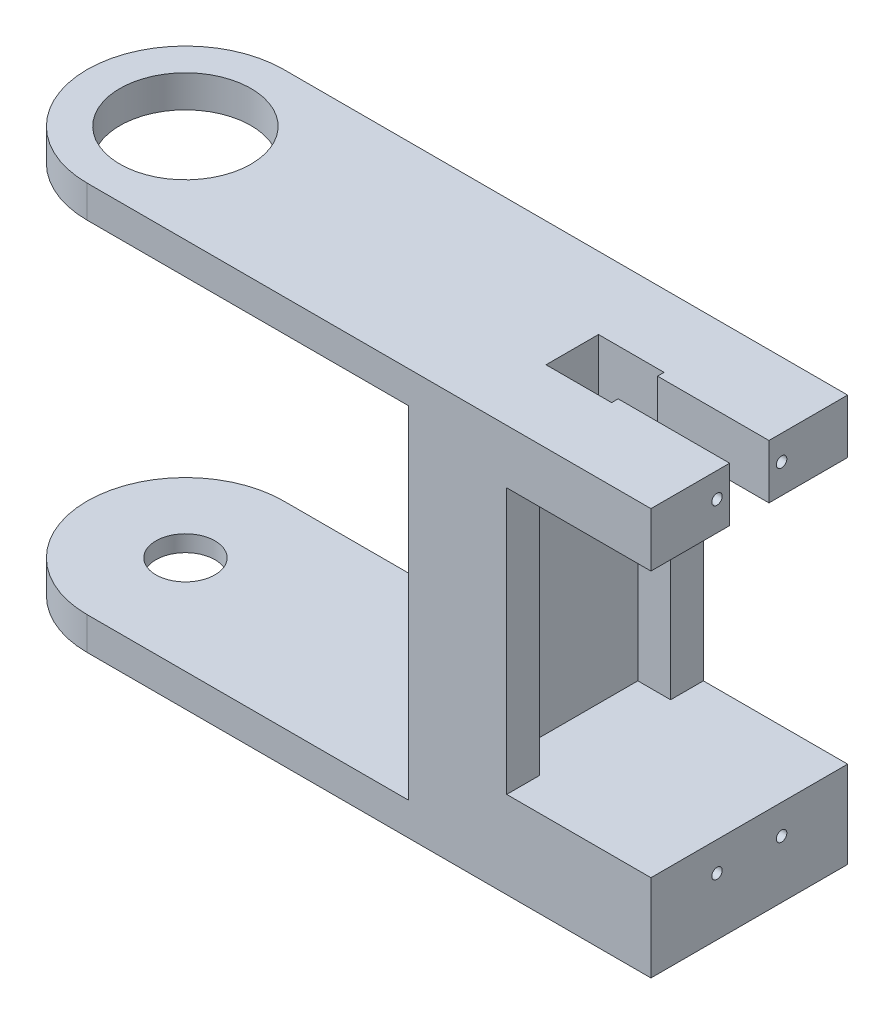
SolidWorks part; units mm, degrees
other "Marquage1"
sketch "Esquisse9" plane through (30.25, -27, 30) normal (0.9363, -0.2766, 0.2166) x (0.221, -0.0157, -0.9752)
ref_plane "Plan de face" through (0, 0, 0) normal (0, 0, 1) x (1, 0, 0)
ref_plane "Plan de dessus" through (0, 0, 0) normal (0, 1, 0) x (1, 0, 0)
ref_plane "Plan de droite" through (0, 0, 0) normal (1, 0, 0) x (0, 0, -1)
sketch "Esquisse1" plane through (0, 0, 0) normal (0, 0, 1) x (1, 0, 0)
  line L1 (-30.25, 32) -> (30.25, 32)
  line L2 (-30.25, 32) -> (-30.25, -32)
  line L3 (-30.25, -32) -> (30.25, -32)
  line L4 (30.25, 32) -> (30.25, -32)
  line L5 (-30.25, 32) -> (30.25, -32) construction
  line L6 (-30.25, -32) -> (30.25, 32) construction
  point P0 (0, 0)
  dimension "D1" = 60.5
  dimension "D2" = 64
extrude "Boss.-Extru.1" add sketch "Esquisse1" along normal blind 30
sketch "Esquisse2" plane through (30.25, 0, 0) normal (1, 0, 0) x (0, 0, -1)
  line L0 (-15, 32) -> (-15, -32) construction
  line L1 (-30, 32) -> (0, 32) construction
  line L2 (-30, -32) -> (0, -32) construction
  circle A0 centre (-15, -17) radius 4.5
  point P8 (-15, -17)
  dimension "D1" = 15
  dimension "D2" = 9
extrude "Enlèv. mat.-Extru.1" cut sketch "Esquisse2" against normal blind 32
sketch "Esquisse4" plane through (0, 0, 30) normal (0, 0, 1) x (1, 0, 0)
  line L0 (0, 0) -> (0, -11.7818) construction
  line L1 (-25.55, -56.5577) -> (25.55, -56.5577)
  line L2 (-25.55, -56.5577) -> (-25.55, 27)
  line L3 (-25.55, 27) -> (25.55, 27)
  line L4 (25.55, -56.5577) -> (25.55, 27)
  line L5 (30.25, 32) -> (-30.25, 32) construction
  dimension "D1" = 51.1
  dimension "D2" = 5
extrude "Enlèv. mat.-Extru.2" cut sketch "Esquisse4" against normal up to surface (30 mm away) up to face at (0, 0, 0)
sketch "Esquisse5" plane through (30.25, 0, 0) normal (1, 0, 0) x (0, 0, -1)
  circle A0 centre (-15, -17) radius 10.5
  dimension "D1" = 21
extrude "Enlèv. mat.-Extru.3" cut sketch "Esquisse5" against normal blind 2
sketch "Esquisse6" plane through (-25.55, 0, 0) normal (1, 0, 0) x (0, 0, -1)
  circle A0 centre (-15, -17) radius 10
extrude "Enlèv. mat.-Extru.4" cut sketch "Esquisse6" against normal up to surface (4.7 mm away) up to face at (-30.25, 0, 15)
sketch "Esquisse7" plane through (0, 0, 30) normal (0, 0, 1) x (1, 0, 0)
  line L0 (0, 0) -> (0, 32.5445) construction
  line L2 (-30.25, 32) -> (16.75, 32)
  line L3 (-30.25, 32) -> (-30.25, 89)
  line L4 (-30.25, 89) -> (16.75, 89)
  line L5 (16.75, 32) -> (16.75, 89)
  dimension "D1" = 57
  dimension "D2" = 47
extrude "Boss.-Extru.2" add sketch "Esquisse7" against normal up to surface (30 mm away) up to face at (0, -1.25, 0)
sketch "Esquisse8" plane through (0, 0, 30) normal (0, 0, 1) x (1, 0, 0)
  line L0 (-15.25, 90.392) -> (-15.25, 19.4965) construction
  line L1 (-30.25, 89) -> (-30.25, -32) construction
  line L2 (16.75, 60.5) -> (-55.9253, 60.5) construction
  line L3 (16.75, 32) -> (16.75, 89) construction
  line L4 (30.25, 32) -> (16.75, 32) construction
  line L6 (-15.25, 80.75) -> (11.75, 80.75)
  line L7 (-15.25, 80.75) -> (-15.25, 40.25)
  line L8 (-15.25, 40.25) -> (11.75, 40.25)
  line L10 (11.75, 40.25) -> (11.75, 32)
  line L11 (11.75, 101.1498) -> (21.75, 101.1498)
  line L12 (11.75, 101.1498) -> (11.75, 80.75)
  line L13 (11.75, 32) -> (21.75, 32)
  line L14 (21.75, 101.1498) -> (21.75, 32)
  dimension "D1" = 15
  dimension "D2" = 28.5
  dimension "D3" = 28.5
  dimension "D4" = 40.5
  dimension "D5" = 27
  dimension "D6" = 10
extrude "Enlèv. mat.-Extru.5" cut sketch "Esquisse8" against normal up to surface (30 mm away) up to face at (3.35, 16.8, 0)
sketch "Esquisse10" plane through (0, 80.75, 0) normal (0, -1, 0) x (1, 0, 0)
  line L0 (-1.75, 30) -> (-1.75, -1.0034) construction
  line L1 (-15.25, 15) -> (11.75, 15) construction
  line L2 (5.75, 0) -> (11.75, 0) construction
  line L4 (-15.25, 0) -> (11.75, 0)
  line L5 (11.75, 0) -> (11.75, 30)
  line L6 (11.75, 30) -> (-15.25, 30)
  line L7 (-15.25, 30) -> (-15.25, 0)
  line L8 (-15.25, 0) -> (-9.25, 0) construction
  line L9 (11.75, 0) -> (11.75, 30) construction
  line L10 (11.75, 30) -> (-15.25, 30) construction
  line L11 (-15.25, 30) -> (-15.25, 0) construction
  line L15 (-5.25, 11) -> (-5.25, 12)
  line L16 (-15.25, 19) -> (-5.25, 19)
  line L17 (-15.25, 19) -> (-15.25, 11)
  line L18 (-15.25, 11) -> (-5.25, 11)
  line L19 (34.75, 18) -> (34.75, 12)
  line L21 (-5.25, 19) -> (-5.25, 18)
  line L22 (-5.25, 18) -> (34.75, 18)
  line L24 (-5.25, 12) -> (34.75, 12)
  dimension "D2" = 6
  dimension "D4" = 10
  dimension "D1" = 0
extrude "Enlèv. mat.-Extru.6" cut sketch "Esquisse10" against normal up to surface (8.25 mm away) contours L17 L18 L15 L24 L19 L22 L21 L16 up to face at (-9.25, 89, 15)
sketch "Esquisse11" plane through (-15.25, 0, 0) normal (1, 0, 0) x (0, 0, -1)
  line L0 (-15, 103.0984) -> (-15, 64.9016) construction
  line L2 (0, 40.25) -> (-30, 40.25) construction
  line L3 (-30, 80.75) -> (-25, 80.75)
  line L4 (-30, 80.75) -> (-30, 40.25)
  line L5 (-30, 40.25) -> (-25, 40.25)
  line L6 (-25, 80.75) -> (-25, 40.25)
  line L7 (0, 40.25) -> (-5, 40.25)
  line L8 (-5, 80.75) -> (-5, 40.25)
  line L9 (0, 80.75) -> (-5, 80.75)
  line L10 (0, 80.75) -> (0, 40.25)
  point P3 (-15, 84)
  dimension "D1" = 5
extrude "Boss.-Extru.3" add sketch "Esquisse11" along normal blind 5
sketch "Esquisse12" plane through (11.75, 0, 0) normal (1, 0, 0) x (0, 0, -1)
  line L0 (-15, 89) -> (-15, 40.25) construction
  line L1 (-19, 89) -> (-11, 89) construction
  line L2 (0, 40.25) -> (-30, 40.25) construction
  line L3 (0, 80.75) -> (-12, 80.75) construction
  line L4 (-25, 60.5) -> (3.7732, 60.5) construction
  line L5 (-25, 40.25) -> (-25, 80.75) construction
  circle A0 centre (-19.925, 85.21) radius 0.5
  circle A1 centre (-10.075, 85.21) radius 0.5
  circle A2 centre (-10.075, 35.79) radius 0.5
  circle A3 centre (-19.925, 35.79) radius 0.5
  point P6 (-10.075, 85.21)
  point P9 (-19.925, 35.79)
  point P10 (-19.925, 85.21)
  point P15 (-10.075, 35.79)
  dimension "D3" = 1
  dimension "D1" = 4.46
  dimension "D2" = 4.925
  dimension "D4" = 4.925
  dimension "D5" = 4.46
extrude "Enlèv. mat.-Extru.7" cut sketch "Esquisse12" against normal blind 15
hole_wizard "Trou taraudé M2x0.42" positions "Esquisse3D2" profile "Esquisse14" tap size "M2x0.4" standard "Ansi Metric"
sketch3d "Esquisse3D2"
  line L0 (-3.25, 85.21, 19.925) -> (11.75, 85.21, 19.925) construction
  line L1 (-3.25, 85.21, 10.075) -> (11.75, 85.21, 10.075) construction
  line L2 (-3.25, 35.79, 10.075) -> (11.75, 35.79, 10.075) construction
  line L3 (-3.25, 35.79, 19.925) -> (11.75, 35.79, 19.925) construction
  point P0 (11.75, 85.21, 19.925)
  point P4 (11.75, 85.21, 10.075)
  point P8 (11.75, 35.79, 10.075)
  point P12 (11.75, 35.79, 19.925)
cosmetic thread "Filetage de perçage5" parameters "D1"=15, "D2"=2
cosmetic thread "Filetage de perçage6" parameters "D1"=15, "D2"=2
cosmetic thread "Filetage de perçage7" parameters "D1"=15, "D2"=2
cosmetic thread "Filetage de perçage8" parameters "D1"=15, "D2"=2
sketch "Esquisse14" plane through (11.75, 85.21, 19.925) normal (0, 1, 0) x (0, 0, -1)
  line L0 (0, 0) -> (0, 17.4807)
  line L1 (0, 17.4807) -> (0.8, 17)
  line L2 (0.8, 17) -> (0.8, 0)
  line L5 (0.8, 0) -> (0, 0)
  line L10 (0, 17.4807) -> (-0.8, 17) construction
  line L11 (0, -6.35) -> (0, 107.95) construction
  dimension "Diamètre du trou pour taraudage" = 1.6
  dimension "Profondeur du trou pour taraudage" = 17
  dimension "Angle de pointe" = 118
sketch "Esquisse15" plane through (-30.25, 0, 0) normal (-1, 0, 0) x (0, 0, 1)
  line L0 (30, -32) -> (0, -32) construction
  line L1 (40, -17) -> (30, -17)
  line L2 (0, -17) -> (-10, -17)
  arc A0 (5, -17) -> (25, -17) centre (15, -17) ccw construction
  arc A1 (0, -17) -> (30, -17) centre (15, -17) ccw
  arc A2 (-10, -17) -> (40, -17) centre (15, -17) ccw
  dimension "D1" = 20
  dimension "D2" = 50
extrude "Enlèv. mat.-Extru.8" cut sketch "Esquisse15" against normal up to surface (60.5 mm away) up to face at (30.25, -6.5, 15)
sketch "Esquisse17" plane through (-15.25, 0, 0) normal (1, 0, 0) x (0, 0, -1)
  line L0 (-15, 89) -> (-15, 40.25) construction
  line L1 (-19, 89) -> (-11, 89) construction
  line L2 (0, 40.25) -> (-30, 40.25) construction
  line L3 (-5, 70.15) -> (-34.9076, 70.15) construction
  line L4 (-5, 80.75) -> (-5, 40.25) construction
  line L5 (-25, 40.25) -> (-25, 80.75) construction
  line L6 (-5, 40.25) -> (-25, 40.25) construction
  circle A0 centre (-15, 70.15) radius 9.25
  point P14 (-15, 70.15)
  dimension "D1" = 10
  dimension "D2" = 29.9
sketch "Esquisse21" plane through (-30.25, 0, 0) normal (-1, 0, 0) x (0, 0, 1)
  circle A0 centre (15, 70.15) radius 9.25 construction
  circle A1 centre (15, 70.15) radius 9.25 construction
  circle A2 centre (15, 70.15) radius 1
  point P4 (15, 70.15)
sketch "Esquisse22" plane through (0, 0, 30) normal (0, 0, 1) x (1, 0, 0)
  line L0 (25.55, 27) -> (-25.55, 27) construction
  line L1 (39.5686, -40.8758) -> (-43.4034, -40.8758)
  line L2 (39.5686, -40.8758) -> (39.5686, 27)
  line L3 (39.5686, 27) -> (-43.4034, 27)
  line L4 (-43.4034, -40.8758) -> (-43.4034, 27)
extrude "Enlèv. mat.-Extru.10" cut sketch "Esquisse22" against normal up to surface (30 mm away) up to face at (1.8929, 33.5714, 0)
sketch "Esquisse23" plane through (0, 0, 0) normal (0, 0, -1) x (-1, 0, 0)
  line L0 (30.25, 58) -> (46.9038, 58) construction
  line L1 (30.25, 89) -> (30.25, 27) construction
  line L2 (30.25, 32) -> (85.25, 32)
  line L3 (30.25, 89) -> (85.25, 89)
  line L4 (30.25, 89) -> (30.25, 84.1)
  line L5 (30.25, 84.1) -> (85.25, 84.1)
  line L6 (85.25, 89) -> (85.25, 84.1)
  line L7 (85.25, 27) -> (85.25, 32)
  line L8 (30.25, 27) -> (85.25, 27)
  line L9 (30.25, 27) -> (30.25, 32)
  line L10 (30.25, 27) -> (-30.25, 27) construction
  dimension "D1" = 4.9
  dimension "D2" = 55
  dimension "D3" = 5
  dimension "D4" = 52.1
extrude "Boss.-Extru.4" add sketch "Esquisse23" against normal up to surface (30 mm away) up to face at (2.65, 53.8, 30)
sketch "Esquisse24" plane through (0, 27, 0) normal (0, -1, 0) x (1, 0, 0)
  line L0 (-85.25, 15) -> (-94.2291, 15) construction
  line L2 (-74.25, 35) -> (-74.25, -10.9716) construction
  line L3 (-30.25, 30) -> (-30.25, 0) construction
  line L4 (-30.25, 30) -> (-30.25, 0)
  circle A0 centre (-74.25, 15) radius 10
  dimension "D1" = 20
  dimension "D2" = 44
extrude "Enlèv. mat.-Extru.11" cut sketch "Esquisse24" against normal up to surface (62 mm away) contours A0
sketch "Esquisse25" plane through (0, 27, 0) normal (0, -1, 0) x (1, 0, 0)
  line L0 (30.25, 30) -> (-85.25, 30) construction
  line L1 (-85.25, 0) -> (30.25, 0) construction
  line L2 (-74.25, 44.1348) -> (-74.25, 30)
  line L3 (-74.25, 0) -> (-74.25, -14.1348)
  arc A0 (-74.25, 30) -> (-74.25, 0) centre (-74.25, 15) ccw
  arc A1 (-74.25, 44.1348) -> (-74.25, -14.1348) centre (-74.25, 15) ccw
extrude "Enlèv. mat.-Extru.12" cut sketch "Esquisse25" against normal up to surface (62 mm away) up to face at (-74.25, 89, 25)
sketch "Esquisse26" plane through (0, 27, 0) normal (0, -1, 0) x (1, 0, 0)
  circle A0 centre (-74.25, 15) radius 4.5
  circle A1 centre (-74.25, 15) radius 10.5
extrude "Boss.-Extru.5" add sketch "Esquisse26" against normal up to surface (5 mm away) up to face at (-74.25, 32, 25)
sketch "Esquisse27" plane through (0, 27, 0) normal (0, -1, 0) x (1, 0, 0)
  circle A0 centre (-74.25, 15) radius 10.5
extrude "Enlèv. mat.-Extru.13" cut sketch "Esquisse27" against normal offset from surface (2.5 mm away) 2.5 up to face at (-63.4171, 32, 15)
sketch "Esquisse28" plane through (0, 32, 0) normal (0, 1, 0) x (1, 0, 0)
  line L1 (11.75, 0) -> (33.2878, 0)
  line L2 (11.75, 0) -> (11.75, -33.2244)
  line L3 (11.75, -33.2244) -> (33.2878, -33.2244)
  line L4 (33.2878, 0) -> (33.2878, -33.2244)
extrude "Enlèv. mat.-Extru.14" cut sketch "Esquisse28" against normal up to surface (5 mm away) up to face at (-63.75, 27, 15)
sketch "Esquisse29" plane through (0, 0, 0) normal (0, 0, -1) x (-1, 0, 0)
  line L0 (74.25, 32) -> (30.25, 32) construction
  line L1 (30.25, 84.1) -> (25.25, 84.1)
  line L2 (30.25, 84.1) -> (30.25, 32)
  line L3 (30.25, 32) -> (25.25, 32)
  line L4 (25.25, 84.1) -> (25.25, 32)
  dimension "D1" = 5
extrude "Enlèv. mat.-Extru.15" cut sketch "Esquisse29" against normal up to surface (30 mm away) up to face at (-27.5833, 58.85, 30)
sketch "Esquisse31" plane through (0, 27, 0) normal (0, -1, 0) x (1, 0, 0)
  line L0 (-82.4117, 21.6059) -> (-85.25, 25.198)
  line L1 (-74.25, 4.5) -> (-85.25, 4.802)
  arc A0 (-85.25, 25.198) -> (-85.25, 4.802) centre (-74.25, 15) ccw
  arc A1 (-85.25, 4.802) -> (-74.25, 0) centre (-74.25, 15) ccw construction
  arc A2 (-82.4117, 21.6059) -> (-74.25, 4.5) centre (-74.25, 15) ccw
  circle A3 centre (-74.25, 15) radius 10.5 construction
  circle M1 centre (-74.25, 15) radius 10.5
  line M6 (-85.25, 25.198) -> (-85.25, 4.802)
extrude "Boss.-Extru.6" add sketch "Esquisse31" against normal up to surface (62 mm away) contours L1 L0 M1 M6 | A0 M6 up to face at (-74.25, 89, 25)
sketch "Esquisse32" plane through (0.0675, 0, 2.4599) normal (-0.0274, 0, -0.9996) x (-0.9996, 0, 0.0274)
  line L0 (85.3497, 32) -> (74.222, 32) construction
  line L1 (74.9218, 84.1) -> (113.711, 84.1)
  line L2 (74.9218, 84.1) -> (74.9218, 32)
  line L3 (74.9218, 32) -> (113.711, 32)
  line L4 (113.711, 84.1) -> (113.711, 32)
extrude "Enlèv. mat.-Extru.16" cut sketch "Esquisse32" against normal up to surface (24.429 mm away)
sketch "Esquisse33" plane through (0, 32, 0) normal (0, 1, 0) x (1, 0, 0)
  line L3 (-74.25, -30) -> (-25.25, -30)
  line L4 (-25.25, -30) -> (-25.25, 0)
  line L5 (-25.25, 0) -> (-74.25, 0)
  line L6 (-74.25, -30) -> (-25.25, -30)
  line L7 (-25.25, -30) -> (-25.25, 0)
  line L8 (-25.25, 0) -> (-74.25, 0)
  arc A1 (-74.25, 0) -> (-74.25, -30) centre (-74.25, -15) ccw
  arc A2 (-74.25, 0) -> (-74.25, -30) centre (-74.25, -15) ccw
  dimension "D1" = 0
extrude "Boss.-Extru.7" [suppressed] add sketch "Esquisse33" along normal blind 0.4
sketch "Esquisse34" [suppressed] plane through (0, 32, 0) normal (0, -1, 0) x (1, 0, 0)
  circle A0 centre (-74.25, 15) radius 4.5
extrude "Enlèv. mat.-Extru.17" [suppressed] cut sketch "Esquisse34" against normal up to surface (0.4 mm away)
